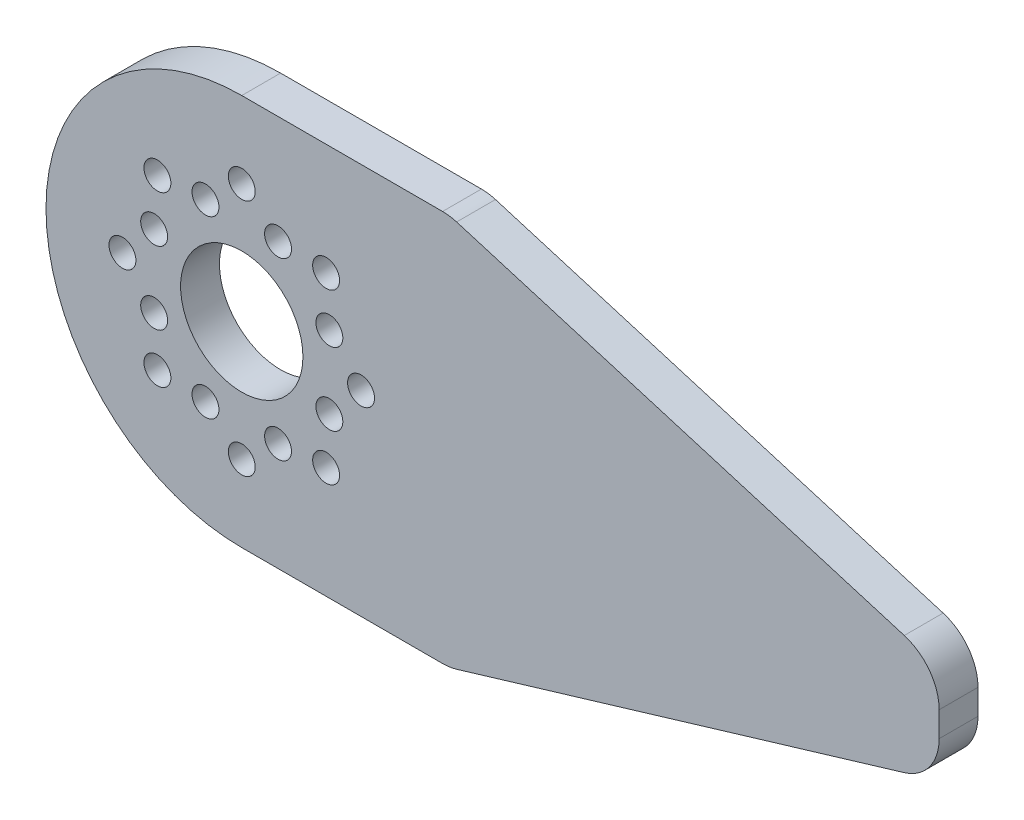
SolidWorks part; units mm, degrees
ref_plane "Front Plane" through (0, 0, 0) normal (0, 0, 1) x (1, 0, 0)
ref_plane "Top Plane" through (0, 0, 0) normal (0, 1, 0) x (1, 0, 0)
ref_plane "Right Plane" through (0, 0, 0) normal (1, 0, 0) x (0, 0, -1)
sketch "Sketch1" plane through (0, 0, 0) normal (0, 0, 1) x (1, 0, 0)
  line L1 (19, 0) -> (76, 0)
  line L3 (19, 32) -> (76, 32)
  line L4 (76, 0) -> (76, 32)
  arc A0 (19, 32) -> (19, 0) centre (19, 16) ccw
  circle A1 centre (25.8943, 22.8943) radius 1.1
  circle A2 centre (19, 25.75) radius 1.1
  circle A3 centre (28.75, 16) radius 1.1
  circle A4 centre (25.8943, 9.1057) radius 1.1
  circle A5 centre (19, 6.25) radius 1.1
  circle A6 centre (12.1057, 9.1057) radius 1.1
  circle A7 centre (9.25, 16) radius 1.1
  circle A8 centre (12.1057, 22.8943) radius 1.1
  circle A9 centre (19, 16) radius 5
  circle A10 centre (26.1601, 18.9658) radius 1.1
  circle A11 centre (21.9658, 23.1601) radius 1.1
  circle A12 centre (26.1601, 13.0342) radius 1.1
  circle A13 centre (21.9658, 8.8399) radius 1.1
  circle A14 centre (16.0342, 8.8399) radius 1.1
  circle A15 centre (11.8399, 13.0342) radius 1.1
  circle A16 centre (11.8399, 18.9658) radius 1.1
  circle A17 centre (16.0342, 23.1601) radius 1.1
  point P24 (19, 16)
  point P42 (19, 16)
  dimension "D3" = 19
  dimension "D6" = 2.2
  dimension "D7" = 10
  dimension "D8" = 7.75
  dimension "D10" = 2.2
  dimension "D1" = 32
  dimension "D2" = 57
  dimension "D4" = 9.75
  dimension "D5" = 8
  dimension "D9" = 22.5
  dimension "D12" = 11.8399
  dimension "D13" = 16.0342
  dimension "D11" = 8
extrude "Boss-Extrude1" add sketch "Sketch1" along normal blind 3.175
sketch "Sketch2" plane through (0, 0, 3.175) normal (0, 0, 1) x (1, 0, 0)
  line L0 (76, 32) -> (76, 20)
  line L1 (76, 0) -> (76, 32) construction
  line L2 (76, 20) -> (36, 32)
  line L3 (76, 32) -> (19, 32) construction
  line L4 (36, 32) -> (76, 32)
  line L5 (76, 0) -> (76, 12)
  line L6 (76, 12) -> (36, 0)
  line L7 (19, 0) -> (76, 0) construction
  line L8 (36, 0) -> (76, 0)
  dimension "D1" = 12
  dimension "D2" = 40
  dimension "D3" = 12
  dimension "D4" = 40
extrude "Cut-Extrude1" cut sketch "Sketch2" against normal blind 3.175
fillet "Fillet1" radius 4 4 edges at (36, 32, 1.5875) (36, 0, 1.5875) (76, 20, 1.5875) (76, 12, 1.5875)
